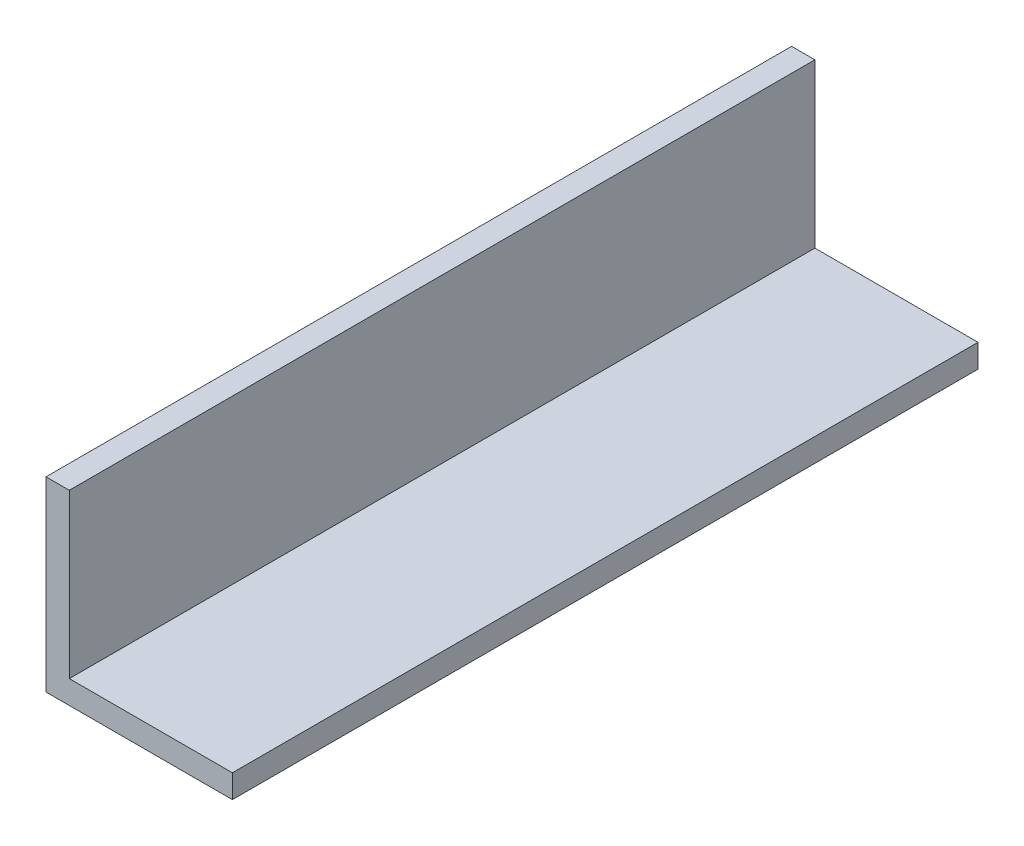
SolidWorks part; units mm, degrees
ref_plane "Front Plane" through (0, 0, 0) normal (0, 0, 1) x (1, 0, 0)
ref_plane "Top Plane" through (0, 0, 0) normal (0, 1, 0) x (1, 0, 0)
ref_plane "Right Plane" through (0, 0, 0) normal (1, 0, 0) x (0, 0, -1)
sketch "Sketch1" plane through (0, 0, 0) normal (0, 0, 1) x (1, 0, 0)
  line L0 (0, 0) -> (0, 25.4)
  line L1 (0, 25.4) -> (3.175, 25.4)
  line L2 (3.175, 25.4) -> (3.175, 3.175)
  line L3 (3.175, 3.175) -> (25.4, 3.175)
  line L4 (25.4, 3.175) -> (25.4, 0)
  line L5 (25.4, 0) -> (0, 0)
  dimension "D1" = 25.4
  dimension "D2" = 3.175
extrude "Boss-Extrude1" add sketch "Sketch1" along normal blind 101.6
